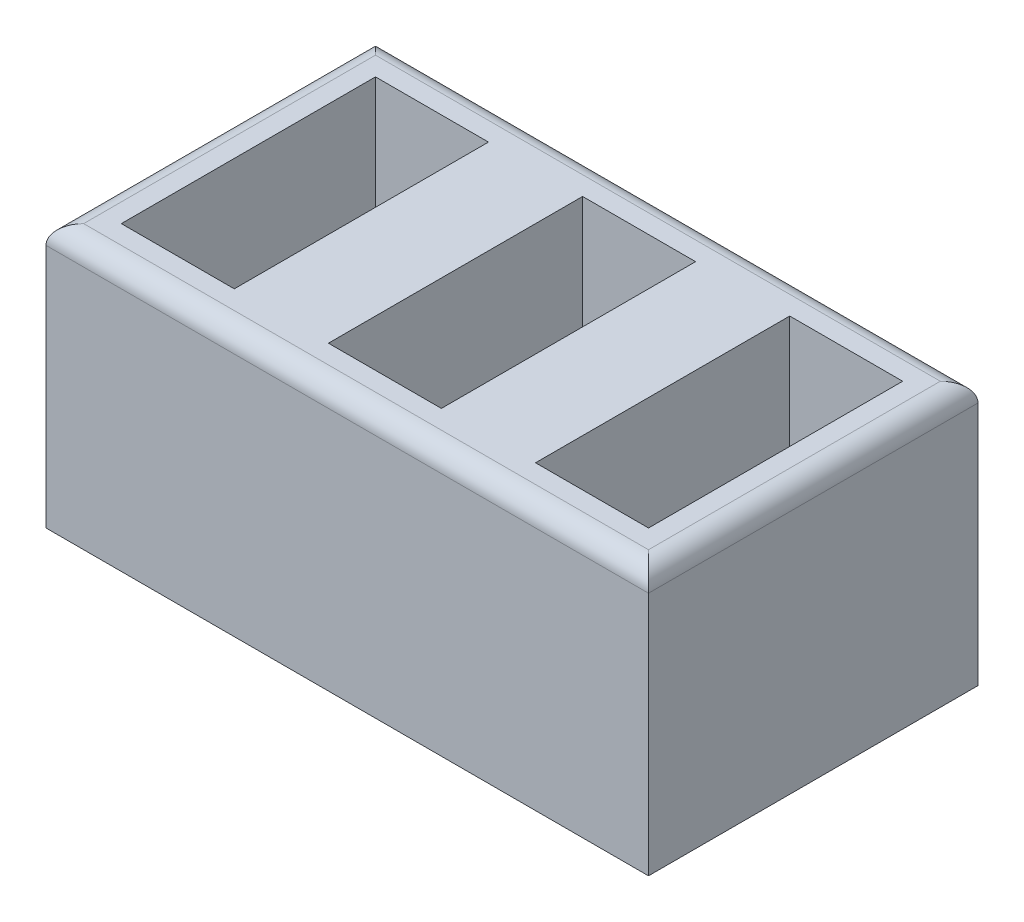
SolidWorks part; units mm, degrees
ref_plane "Front Plane" through (0, 0, 0) normal (0, 0, 1) x (1, 0, 0)
ref_plane "Top Plane" through (0, 0, 0) normal (0, 1, 0) x (1, 0, 0)
ref_plane "Right Plane" through (0, 0, 0) normal (1, 0, 0) x (0, 0, -1)
sketch "Sketch1" plane through (0, 0, 0) normal (0, 1, 0) x (1, 0, 0)
  line L1 (0, 0) -> (32, 0)
  line L2 (0, 0) -> (0, 17.5)
  line L3 (0, 17.5) -> (32, 17.5)
  line L4 (32, 0) -> (32, 17.5)
  dimension "D1" = 17.5
  dimension "D2" = 32
extrude "Boss-Extrude1" add sketch "Sketch1" along normal blind 14
sketch "Sketch2" plane through (0, 14, 0) normal (0, 1, 0) x (1, 0, 0)
  line L0 (0, 17.5) -> (0, 0) construction
  line L1 (2, 15.5) -> (8, 15.5)
  line L2 (2, 15.5) -> (2, 2)
  line L3 (2, 2) -> (8, 2)
  line L4 (8, 15.5) -> (8, 2)
  line L5 (32, 17.5) -> (0, 17.5) construction
  line L6 (0, 0) -> (32, 0) construction
  dimension "D1" = 2
  dimension "D2" = 2
  dimension "D3" = 2
  dimension "D4" = 6
extrude "Cut-Extrude1" cut sketch "Sketch2" against normal blind 13.6
pattern_linear "LPattern1" count 3 spacing 11 along (1, 0, 0) of "Cut-Extrude1"
fillet "Fillet1" radius 1 4 edges at (16, 14, -17.5) (16, 14, 0) (0, 14, -8.75) (32, 14, -8.75)
